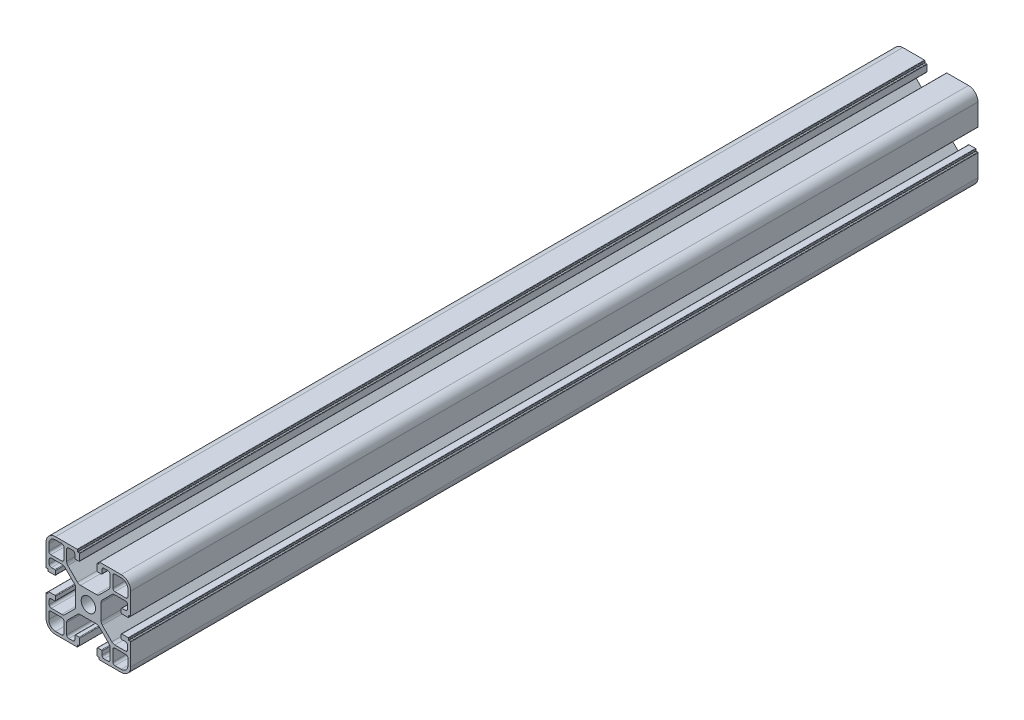
SolidWorks part; units mm, degrees
material "6063-T5"
ref_plane "Front Plane" through (0, 0, 0) normal (0, 0, 1) x (1, 0, 0)
ref_plane "Top Plane" through (0, 0, 0) normal (0, 1, 0) x (1, 0, 0)
ref_plane "Right Plane" through (0, 0, 0) normal (1, 0, 0) x (0, 0, -1)
sketch "Sketch2" plane through (0, 0, 0) normal (0, 0, 1) x (1, 0, 0)
  line L0 (4.5, 0) -> (14.7, 0)
  line L1 (40, 4.5) -> (40, 14.7)
  line L2 (35.5, 40) -> (25.3, 40)
  line L3 (0, 35.5) -> (0, 25.3)
  line L4 (15.9, 1.2) -> (15.9, 4.2)
  line L5 (24.1, 1.2) -> (24.1, 4.2)
  line L6 (38.8, 24.1) -> (35.8, 24.1)
  line L7 (35.5, 24.4) -> (35.5, 26.1)
  line L8 (14, 23.7574) -> (14, 16.2426)
  line L9 (16.2426, 14) -> (23.7574, 14)
  line L10 (26, 16.2426) -> (26, 23.7574)
  line L11 (13.4142, 14.8284) -> (8.9216, 10.3358)
  line L12 (23.7574, 26) -> (16.2426, 26)
  line L13 (4.5, 24.4) -> (4.5, 26.1)
  line L14 (1.2, 24.1) -> (4.2, 24.1)
  line L15 (15.9, 38.8) -> (15.9, 35.8)
  line L16 (14.8284, 26.5858) -> (10.3358, 31.0784)
  line L17 (13.4142, 25.1716) -> (8.9216, 29.6642)
  line L18 (14.8284, 13.4142) -> (10.3358, 8.9216)
  line L19 (25.1716, 13.4142) -> (29.6642, 8.9216)
  line L20 (26.5858, 14.8284) -> (31.0784, 10.3358)
  line L21 (26.5858, 25.1716) -> (31.0784, 29.6642)
  line L22 (25.1716, 26.5858) -> (29.6642, 31.0784)
  line L23 (24.1, 38.8) -> (24.1, 35.8)
  line L24 (14.7, 40) -> (4.5, 40)
  line L25 (25.3, 0) -> (35.5, 0)
  line L26 (38.8, 15.9) -> (35.8, 15.9)
  line L27 (40, 25.3) -> (40, 35.5)
  line L28 (1.2, 15.9) -> (4.2, 15.9)
  line L29 (0, 14.7) -> (0, 4.5)
  line L30 (4.5, 15.6) -> (4.5, 13.9)
  line L31 (35.5, 15.6) -> (35.5, 13.9)
  line L32 (15.6, 35.5) -> (13.9, 35.5)
  line L33 (24.4, 35.5) -> (26.1, 35.5)
  line L34 (15.6, 4.5) -> (13.9, 4.5)
  line L35 (24.4, 4.5) -> (26.1, 4.5)
  line L36 (12.6, 38.5) -> (10.75, 38.5)
  line L37 (1.5, 12.6) -> (1.5, 10.75)
  line L38 (27.4, 1.5) -> (29.25, 1.5)
  line L39 (38.5, 27.4) -> (38.5, 29.25)
  line L40 (38.5, 10.75) -> (38.5, 12.6)
  line L41 (29.25, 38.5) -> (27.4, 38.5)
  line L42 (1.5, 29.25) -> (1.5, 27.4)
  line L43 (10.75, 1.5) -> (12.6, 1.5)
  line L44 (35.8, 26.4) -> (37.5, 26.4)
  line L45 (35.8, 13.6) -> (37.5, 13.6)
  line L46 (4.2, 26.4) -> (2.5, 26.4)
  line L47 (13.6, 35.8) -> (13.6, 37.5)
  line L48 (26.4, 35.8) -> (26.4, 37.5)
  line L49 (4.2, 13.6) -> (2.5, 13.6)
  line L50 (13.6, 4.2) -> (13.6, 2.5)
  line L51 (26.4, 4.2) -> (26.4, 2.5)
  line L52 (9.75, 7.5074) -> (9.75, 2.5)
  line L53 (30.25, 7.5074) -> (30.25, 2.5)
  line L54 (9.75, 37.5) -> (9.75, 32.4926)
  line L55 (30.25, 37.5) -> (30.25, 32.4926)
  line L56 (32.4926, 30.25) -> (37.5, 30.25)
  line L57 (37.5, 9.75) -> (32.4926, 9.75)
  line L58 (2.5, 30.25) -> (7.5074, 30.25)
  line L59 (2.5, 9.75) -> (7.5074, 9.75)
  line L60 (31.55, 37.7) -> (31.55, 32.55)
  line L61 (32.55, 31.55) -> (37.7, 31.55)
  line L62 (1.3, 35.5) -> (1.3, 32.55)
  line L63 (4.5, 38.7) -> (7.45, 38.7)
  line L64 (32.55, 38.7) -> (35.5, 38.7)
  line L65 (38.7, 35.5) -> (38.7, 32.55)
  line L66 (8.45, 37.7) -> (8.45, 32.55)
  line L67 (2.3, 31.55) -> (7.45, 31.55)
  line L68 (1.3, 7.45) -> (1.3, 4.5)
  line L69 (2.3, 8.45) -> (7.45, 8.45)
  line L70 (8.45, 7.45) -> (8.45, 2.3)
  line L71 (4.5, 1.3) -> (7.45, 1.3)
  line L72 (31.55, 7.45) -> (31.55, 2.3)
  line L73 (32.55, 8.45) -> (37.7, 8.45)
  line L74 (38.7, 7.45) -> (38.7, 4.5)
  line L75 (32.55, 1.3) -> (35.5, 1.3)
  line L77 (14.9, 39.8) -> (14.9, 39.2)
  line L78 (15.1, 39) -> (15.7, 39)
  line L79 (25.1, 39.8) -> (25.1, 39.2)
  line L80 (24.9, 39) -> (24.3, 39)
  line L81 (25.1, 0.2) -> (25.1, 0.8)
  line L82 (24.9, 1) -> (24.3, 1)
  line L83 (14.9, 0.2) -> (14.9, 0.8)
  line L84 (15.1, 1) -> (15.7, 1)
  line L85 (0.2, 25.1) -> (0.8, 25.1)
  line L86 (1, 24.9) -> (1, 24.3)
  line L87 (0.2, 14.9) -> (0.8, 14.9)
  line L88 (1, 15.1) -> (1, 15.7)
  line L89 (39.8, 25.1) -> (39.2, 25.1)
  line L90 (39, 24.9) -> (39, 24.3)
  line L91 (39, 15.7) -> (39, 15.1)
  line L92 (39.2, 14.9) -> (39.8, 14.9)
  circle A0 centre (20, 20) radius 3.4
  arc A1 (1.3, 35.5) -> (4.5, 38.7) centre (4.5, 35.5) cw
  arc A2 (1.3, 4.5) -> (4.5, 1.3) centre (4.5, 4.5) ccw
  arc A3 (38.7, 4.5) -> (35.5, 1.3) centre (35.5, 4.5) cw
  arc A4 (35.5, 38.7) -> (38.7, 35.5) centre (35.5, 35.5) cw
  arc A5 (40, 35.5) -> (35.5, 40) centre (35.5, 35.5) ccw
  arc A6 (35.5, 0) -> (40, 4.5) centre (35.5, 4.5) ccw
  arc A7 (4.5, 0) -> (0, 4.5) centre (4.5, 4.5) cw
  arc A8 (4.5, 40) -> (0, 35.5) centre (4.5, 35.5) ccw
  arc A9 (13.4142, 14.8284) -> (14, 16.2426) centre (12, 16.2426) ccw
  arc A10 (7.5074, 9.75) -> (8.9216, 10.3358) centre (7.5074, 11.75) ccw
  arc A11 (9.75, 7.5074) -> (10.3358, 8.9216) centre (11.75, 7.5074) cw
  arc A12 (30.25, 7.5074) -> (29.6642, 8.9216) centre (28.25, 7.5074) ccw
  arc A13 (14.8284, 13.4142) -> (16.2426, 14) centre (16.2426, 12) cw
  arc A14 (25.1716, 13.4142) -> (23.7574, 14) centre (23.7574, 12) ccw
  arc A15 (32.4926, 9.75) -> (31.0784, 10.3358) centre (32.4926, 11.75) cw
  arc A16 (26.5858, 14.8284) -> (26, 16.2426) centre (28, 16.2426) cw
  arc A17 (32.4926, 30.25) -> (31.0784, 29.6642) centre (32.4926, 28.25) ccw
  arc A18 (26.5858, 25.1716) -> (26, 23.7574) centre (28, 23.7574) ccw
  arc A19 (13.4142, 25.1716) -> (14, 23.7574) centre (12, 23.7574) cw
  arc A20 (7.5074, 30.25) -> (8.9216, 29.6642) centre (7.5074, 28.25) cw
  arc A21 (9.75, 32.4926) -> (10.3358, 31.0784) centre (11.75, 32.4926) ccw
  arc A22 (30.25, 32.4926) -> (29.6642, 31.0784) centre (28.25, 32.4926) cw
  arc A23 (25.1716, 26.5858) -> (23.7574, 26) centre (23.7574, 28) cw
  arc A24 (14.8284, 26.5858) -> (16.2426, 26) centre (16.2426, 28) ccw
  arc A25 (37.7, 8.45) -> (38.7, 7.45) centre (37.7, 7.45) cw
  arc A26 (31.55, 2.3) -> (32.55, 1.3) centre (32.55, 2.3) ccw
  arc A27 (31.55, 7.45) -> (32.55, 8.45) centre (32.55, 7.45) cw
  arc A28 (8.45, 2.3) -> (7.45, 1.3) centre (7.45, 2.3) cw
  arc A29 (1.3, 7.45) -> (2.3, 8.45) centre (2.3, 7.45) cw
  arc A30 (7.45, 8.45) -> (8.45, 7.45) centre (7.45, 7.45) cw
  arc A31 (38.7, 32.55) -> (37.7, 31.55) centre (37.7, 32.55) cw
  arc A32 (31.55, 32.55) -> (32.55, 31.55) centre (32.55, 32.55) ccw
  arc A33 (31.55, 37.7) -> (32.55, 38.7) centre (32.55, 37.7) cw
  arc A34 (7.45, 38.7) -> (8.45, 37.7) centre (7.45, 37.7) cw
  arc A35 (8.45, 32.55) -> (7.45, 31.55) centre (7.45, 32.55) cw
  arc A36 (1.3, 32.55) -> (2.3, 31.55) centre (2.3, 32.55) ccw
  arc A37 (30.25, 2.5) -> (29.25, 1.5) centre (29.25, 2.5) cw
  arc A38 (26.4, 2.5) -> (27.4, 1.5) centre (27.4, 2.5) ccw
  arc A39 (13.6, 2.5) -> (12.6, 1.5) centre (12.6, 2.5) cw
  arc A40 (9.75, 2.5) -> (10.75, 1.5) centre (10.75, 2.5) ccw
  arc A41 (26.4, 37.5) -> (27.4, 38.5) centre (27.4, 37.5) cw
  arc A42 (30.25, 37.5) -> (29.25, 38.5) centre (29.25, 37.5) ccw
  arc A43 (37.5, 26.4) -> (38.5, 27.4) centre (37.5, 27.4) ccw
  arc A44 (37.5, 30.25) -> (38.5, 29.25) centre (37.5, 29.25) cw
  arc A45 (37.5, 13.6) -> (38.5, 12.6) centre (37.5, 12.6) cw
  arc A46 (37.5, 9.75) -> (38.5, 10.75) centre (37.5, 10.75) ccw
  arc A47 (2.5, 9.75) -> (1.5, 10.75) centre (2.5, 10.75) cw
  arc A48 (2.5, 13.6) -> (1.5, 12.6) centre (2.5, 12.6) ccw
  arc A49 (2.5, 26.4) -> (1.5, 27.4) centre (2.5, 27.4) cw
  arc A50 (2.5, 30.25) -> (1.5, 29.25) centre (2.5, 29.25) ccw
  arc A51 (9.75, 37.5) -> (10.75, 38.5) centre (10.75, 37.5) cw
  arc A52 (13.6, 37.5) -> (12.6, 38.5) centre (12.6, 37.5) ccw
  arc A53 (26.1, 35.5) -> (26.4, 35.8) centre (26.1, 35.8) ccw
  arc A54 (24.1, 35.8) -> (24.4, 35.5) centre (24.4, 35.8) ccw
  arc A55 (15.9, 35.8) -> (15.6, 35.5) centre (15.6, 35.8) cw
  arc A56 (13.9, 35.5) -> (13.6, 35.8) centre (13.9, 35.8) cw
  arc A57 (13.9, 4.5) -> (13.6, 4.2) centre (13.9, 4.2) ccw
  arc A58 (15.9, 4.2) -> (15.6, 4.5) centre (15.6, 4.2) ccw
  arc A59 (24.1, 4.2) -> (24.4, 4.5) centre (24.4, 4.2) cw
  arc A60 (26.1, 4.5) -> (26.4, 4.2) centre (26.1, 4.2) cw
  arc A61 (35.5, 13.9) -> (35.8, 13.6) centre (35.8, 13.9) ccw
  arc A62 (35.8, 15.9) -> (35.5, 15.6) centre (35.8, 15.6) ccw
  arc A63 (35.8, 24.1) -> (35.5, 24.4) centre (35.8, 24.4) cw
  arc A64 (35.5, 26.1) -> (35.8, 26.4) centre (35.8, 26.1) cw
  arc A65 (4.5, 13.9) -> (4.2, 13.6) centre (4.2, 13.9) cw
  arc A66 (4.2, 15.9) -> (4.5, 15.6) centre (4.2, 15.6) cw
  arc A67 (4.2, 24.1) -> (4.5, 24.4) centre (4.2, 24.4) ccw
  arc A68 (4.5, 26.1) -> (4.2, 26.4) centre (4.2, 26.1) ccw
  arc A69 (25.3, 0) -> (25.1, 0.2) centre (25.3, 0.2) cw
  arc A70 (25.1, 0.8) -> (24.9, 1) centre (24.9, 0.8) ccw
  arc A71 (24.3, 1) -> (24.1, 1.2) centre (24.3, 1.2) cw
  arc A72 (14.7, 0) -> (14.9, 0.2) centre (14.7, 0.2) ccw
  arc A73 (14.9, 0.8) -> (15.1, 1) centre (15.1, 0.8) cw
  arc A74 (15.7, 1) -> (15.9, 1.2) centre (15.7, 1.2) ccw
  arc A75 (39.8, 14.9) -> (40, 14.7) centre (39.8, 14.7) cw
  arc A76 (39, 15.1) -> (39.2, 14.9) centre (39.2, 15.1) ccw
  arc A77 (38.8, 15.9) -> (39, 15.7) centre (38.8, 15.7) cw
  arc A78 (0, 25.3) -> (0.2, 25.1) centre (0.2, 25.3) ccw
  arc A79 (0.8, 25.1) -> (1, 24.9) centre (0.8, 24.9) cw
  arc A80 (1, 24.3) -> (1.2, 24.1) centre (1.2, 24.3) ccw
  arc A81 (0, 14.7) -> (0.2, 14.9) centre (0.2, 14.7) cw
  arc A82 (0.8, 14.9) -> (1, 15.1) centre (0.8, 15.1) ccw
  arc A83 (1, 15.7) -> (1.2, 15.9) centre (1.2, 15.7) cw
  arc A84 (39, 24.3) -> (38.8, 24.1) centre (38.8, 24.3) cw
  arc A85 (39.2, 25.1) -> (39, 24.9) centre (39.2, 24.9) ccw
  arc A86 (40, 25.3) -> (39.8, 25.1) centre (39.8, 25.3) cw
  arc A87 (24.3, 39) -> (24.1, 38.8) centre (24.3, 38.8) ccw
  arc A88 (25.1, 39.2) -> (24.9, 39) centre (24.9, 39.2) cw
  arc A89 (25.3, 40) -> (25.1, 39.8) centre (25.3, 39.8) ccw
  arc A90 (14.9, 39.2) -> (15.1, 39) centre (15.1, 39.2) ccw
  arc A91 (15.7, 39) -> (15.9, 38.8) centre (15.7, 38.8) cw
  arc A92 (14.7, 40) -> (14.9, 39.8) centre (14.7, 39.8) cw
  point P93 (0, 0)
extrude "Boss-Extrude1" add sketch "Sketch2" along normal blind 400
